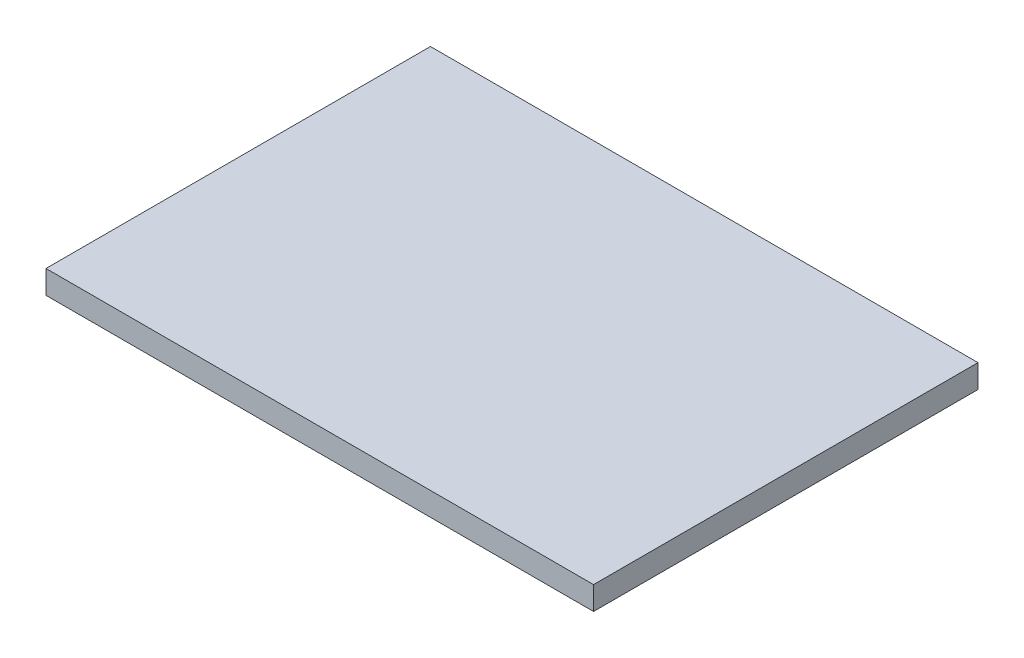
SolidWorks part; units mm, degrees
ref_plane "Front Plane" through (0, 0, 0) normal (0, 0, 1) x (1, 0, 0)
ref_plane "Top Plane" through (0, 0, 0) normal (0, 1, 0) x (1, 0, 0)
ref_plane "Right Plane" through (0, 0, 0) normal (1, 0, 0) x (0, 0, -1)
sketch "Sketch1" plane through (0, 0, 0) normal (0, 1, 0) x (1, 0, 0)
  line L1 (-47, 33) -> (47, 33)
  line L2 (-47, 33) -> (-47, -33)
  line L3 (-47, -33) -> (47, -33)
  line L4 (47, 33) -> (47, -33)
  line L5 (-47, 33) -> (47, -33) construction
  line L6 (-47, -33) -> (47, 33) construction
  point P0 (0, 0)
  dimension "D1" = 94
  dimension "D2" = 66
extrude "Boss-Extrude1" add sketch "Sketch1" along normal blind 4
